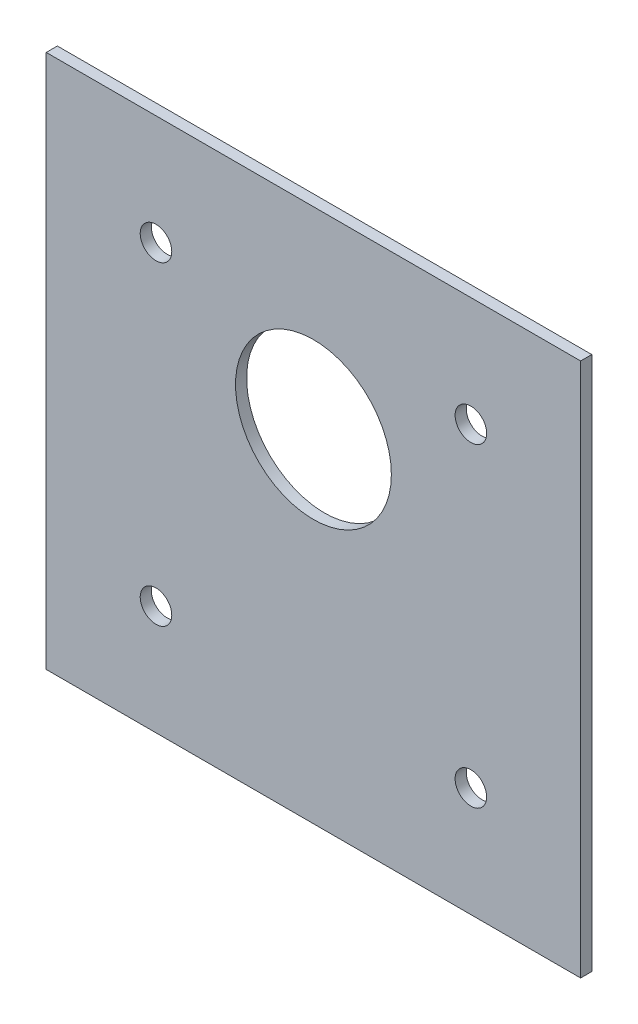
SolidWorks part; units mm, degrees
ref_plane "Front Plane" through (0, 0, 0) normal (0, 0, 1) x (1, 0, 0)
ref_plane "Top Plane" through (0, 0, 0) normal (0, 1, 0) x (1, 0, 0)
ref_plane "Right Plane" through (0, 0, 0) normal (1, 0, 0) x (0, 0, -1)
sketch "Sketch1" plane through (0, 0, 0) normal (0, 0, 1) x (1, 0, 0)
  line L0 (0, -1) -> (-19.0885, -1) construction
  line L1 (-52, 52) -> (52, 52)
  line L2 (-52, 52) -> (-52, -52)
  line L3 (-52, -52) -> (52, -52)
  line L4 (52, 52) -> (52, -52)
  line L5 (-42.4264, 42.4264) -> (52, -52) construction
  line L6 (-52, -52) -> (52, 52) construction
  circle A0 centre (0, 20) radius 21
  circle A1 centre (0, 0) radius 60 construction
  circle A2 centre (-42.4264, 42.4264) radius 4.25
  circle A3 centre (42.4264, 42.4264) radius 4.25
  circle A4 centre (42.4264, -42.4264) radius 4.25
  circle A5 centre (-42.4264, -42.4264) radius 4.25
  point P0 (0, 0)
  dimension "D2" = 120
  dimension "D3" = 8.5
  dimension "D4" = 42
  dimension "D1" = 104
  dimension "D5" = 20
extrude "Boss-Extrude1" add sketch "Sketch1" along normal blind 3
sketch "Sketch2" plane through (0, 0, 0) normal (0, 0, -1) x (-1, 0, 0)
  line L0 (72, 72) -> (72, -72)
  line L1 (-52, 52) -> (52, 52)
  line L2 (-52, 52) -> (-52, -52)
  line L3 (-52, -52) -> (52, -52)
  line L4 (52, 52) -> (52, -52)
  line L5 (-72, -72) -> (72, -72)
  line L6 (-72, 72) -> (-72, -72)
  line L7 (-72, 72) -> (72, 72)
  dimension "D1" = 20
extrude "Boss-Extrude2" add sketch "Sketch2" against normal blind 3
sketch "Sketch3" plane through (0, 0, 0) normal (0, 0, -1) x (-1, 0, 0)
  line L2 (72, -72) -> (72, 72)
  line L3 (72, 72) -> (-72, 72)
  line L4 (-72, -72) -> (-72, 72)
